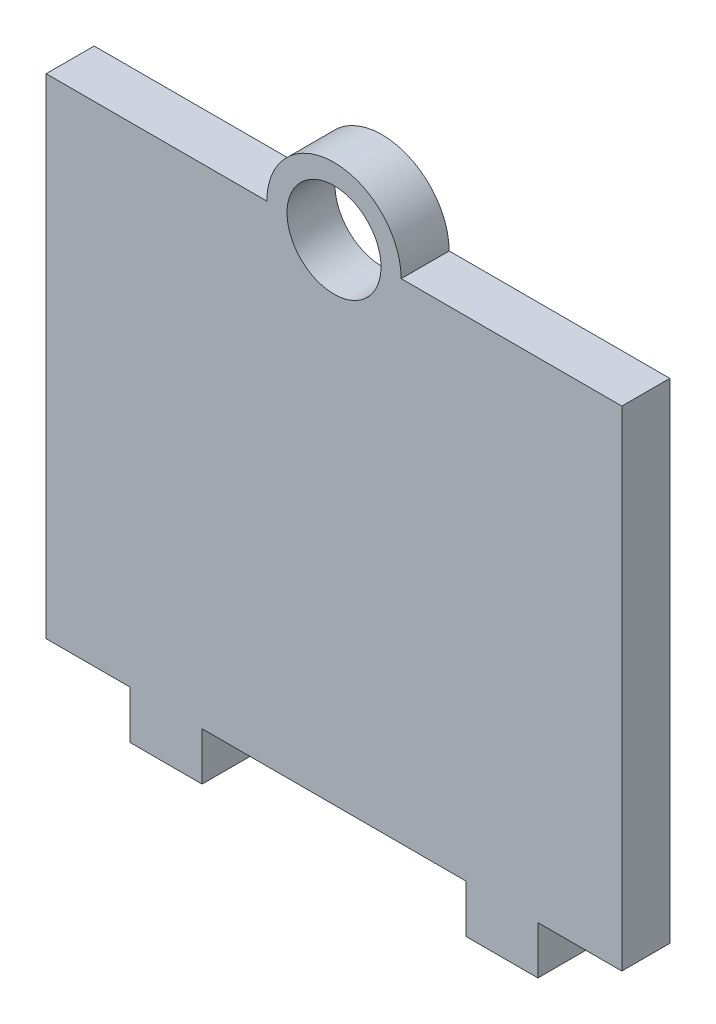
SolidWorks part; units mm, degrees
material "Acrylic (Medium-high impact)"
ref_plane "Front Plane" through (0, 0, 0) normal (0, 0, 1) x (1, 0, 0)
ref_plane "Top Plane" through (0, 0, 0) normal (0, 1, 0) x (1, 0, 0)
ref_plane "Right Plane" through (0, 0, 0) normal (1, 0, 0) x (0, 0, -1)
sketch "Sketch1" plane through (0, 0, 0) normal (0, 0, 1) x (1, 0, 0)
  line L0 (53.975, 0) -> (34.925, 0) construction
  line L1 (-76.2, 142.24) -> (-17.78, 142.24)
  line L2 (-76.2, 142.24) -> (-76.2, 12.7)
  line L3 (-76.2, 12.7) -> (-53.975, 12.7)
  line L4 (76.2, 142.24) -> (76.2, 12.7)
  line L5 (53.975, 0) -> (53.975, 12.7) construction
  line L6 (34.925, 0) -> (34.925, 12.7) construction
  line L7 (-34.925, 0) -> (-53.975, 0) construction
  line L8 (-34.925, 0) -> (-34.925, 12.7) construction
  line L9 (-53.975, 0) -> (-53.975, 12.7) construction
  line L10 (53.975, 0) -> (34.925, 0)
  line L11 (53.975, 0) -> (53.975, 12.7)
  line L12 (34.925, 0) -> (34.925, 12.7)
  line L13 (-34.925, 0) -> (-53.975, 0)
  line L14 (-34.925, 0) -> (-34.925, 12.7)
  line L15 (-53.975, 0) -> (-53.975, 12.7)
  line L16 (-34.925, 12.7) -> (34.925, 12.7)
  line L17 (53.975, 12.7) -> (76.2, 12.7)
  line L18 (17.78, 142.24) -> (76.2, 142.24)
  line L19 (76.2, 12.7) -> (76.2, 0) construction
  circle A0 centre (0, 142.24) radius 12.446
  arc A1 (17.78, 142.24) -> (-17.78, 142.24) centre (0, 142.24) ccw
  dimension "D1" = 24.892
  dimension "D2" = 35.56
extrude "Extrude1" add sketch "Sketch1" against normal blind 12.7
